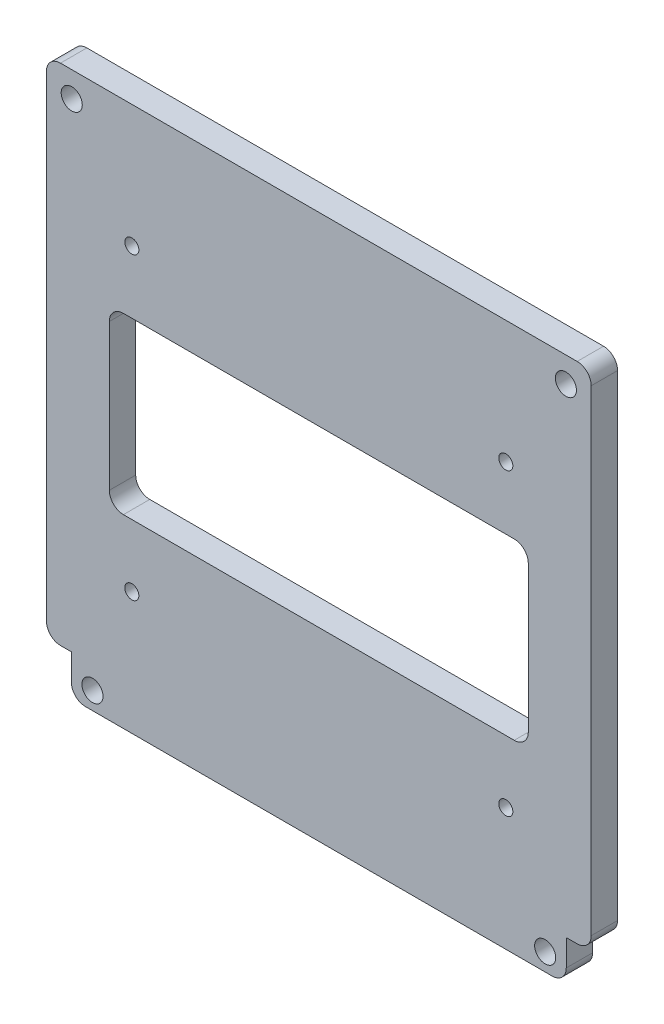
SolidWorks part; units mm, degrees
ref_plane "Front Plane" through (0, 0, 0) normal (0, 0, 1) x (1, 0, 0)
ref_plane "Top Plane" through (0, 0, 0) normal (0, 1, 0) x (1, 0, 0)
ref_plane "Right Plane" through (0, 0, 0) normal (1, 0, 0) x (0, 0, -1)
sketch "Sketch1" plane through (0, 0, 0) normal (0, 0, 1) x (1, 0, 0)
  line L1 (-87.7721, 78.0317) -> (10.6529, 78.0317)
  line L2 (-87.7721, 78.0317) -> (-87.7721, -20.3933)
  line L3 (-87.7721, -20.3933) -> (10.6529, -20.3933)
  line L4 (10.6529, 78.0317) -> (10.6529, -20.3933)
  line L5 (-87.7721, 78.0317) -> (10.6529, -20.3933) construction
  line L6 (-87.7721, -20.3933) -> (10.6529, 78.0317) construction
  point P0 (-38.5596, 28.8192)
  dimension "D1" = 98.425
  dimension "D2" = 98.425
extrude "Boss-Extrude1" add sketch "Sketch1" along normal blind 4.7625
sketch "Sketch4" plane through (0, 0, 0) normal (0, 0, -1) x (-1, 0, 0)
  line L0 (87.7721, -20.3933) -> (-10.6529, 78.0317) construction
  line L1 (0.7136, 66.1572) -> (0.7136, 38.3442) construction
  line L2 (76.4056, 13.0712) -> (0.7136, 13.0712)
  line L3 (76.4056, 13.0712) -> (76.4056, 44.5672)
  line L4 (76.4056, 44.5672) -> (0.7136, 44.5672)
  line L5 (0.7136, 13.0712) -> (0.7136, 44.5672)
  line L6 (76.4056, 13.0712) -> (0.7136, 44.5672) construction
  line L7 (-10.6529, -20.3933) -> (-10.6529, 78.0317) construction
  line L8 (-10.6529, 78.0317) -> (87.7721, 78.0317) construction
  line L9 (76.4056, 44.5672) -> (0.7136, 13.0712) construction
  line L12 (4.7776, 57.6482) -> (4.7776, 54.0922) construction
  circle A0 centre (72.3416, 55.8702) radius 1.27
  circle A1 centre (72.3416, 1.7682) radius 1.27
  circle A2 centre (4.7776, 55.8702) radius 1.27
  circle A3 centre (4.7776, 1.7682) radius 1.27
  circle A4 centre (-6.0809, 73.4597) radius 1.905
  circle A5 centre (83.2001, 73.4597) radius 1.905
  circle A6 centre (-2.3344, -17.2183) radius 1.905
  circle A7 centre (79.4536, -17.2183) radius 1.905
  point P2 (38.5596, 28.8192)
  dimension "D3" = 2.54
  dimension "D4" = 3.81
  dimension "D7" = 3.81
  dimension "D8" = 3.81
  dimension "D1" = 31.496
  dimension "D5" = 4.572
  dimension "D6" = 4.572
extrude "Cut-Extrude1" cut sketch "Sketch4" against normal up to next
sketch "Sketch5" plane through (0, 0, 0) normal (0, 0, -1) x (-1, 0, 0)
  line L0 (87.7721, -20.3933) -> (-10.6529, -20.3933) construction
  line L1 (-6.1444, -13.0908) -> (-10.6529, -13.0908)
  line L2 (-6.1444, -13.0908) -> (-6.1444, -20.3933)
  line L3 (-6.1444, -20.3933) -> (-10.6529, -20.3933)
  line L4 (-10.6529, -13.0908) -> (-10.6529, -20.3933)
  line L6 (83.2636, -13.0908) -> (87.7721, -13.0908)
  line L7 (83.2636, -13.0908) -> (83.2636, -20.3933)
  line L8 (83.2636, -20.3933) -> (87.7721, -20.3933)
  line L9 (87.7721, -13.0908) -> (87.7721, -20.3933)
extrude "Cut-Extrude2" cut sketch "Sketch5" against normal up to next
fillet "Fillet1" radius 2.54 2 edges at (-87.7721, 78.0317, 2.3813) (10.6529, 78.0317, 2.3813)
fillet "Fillet3" radius 2.54 4 edges at (-76.4056, 13.0712, 2.3813) (-76.4056, 44.5672, 2.3813) (-0.7136, 13.0712, 2.3813) (-0.7136, 44.5672, 2.3813)
fillet "Fillet4" radius 2.54 4 edges at (-83.2636, -20.3933, 2.3813) (-87.7721, -13.0908, 2.3813) (6.1444, -20.3933, 2.3813) (10.6529, -13.0908, 2.3813)
